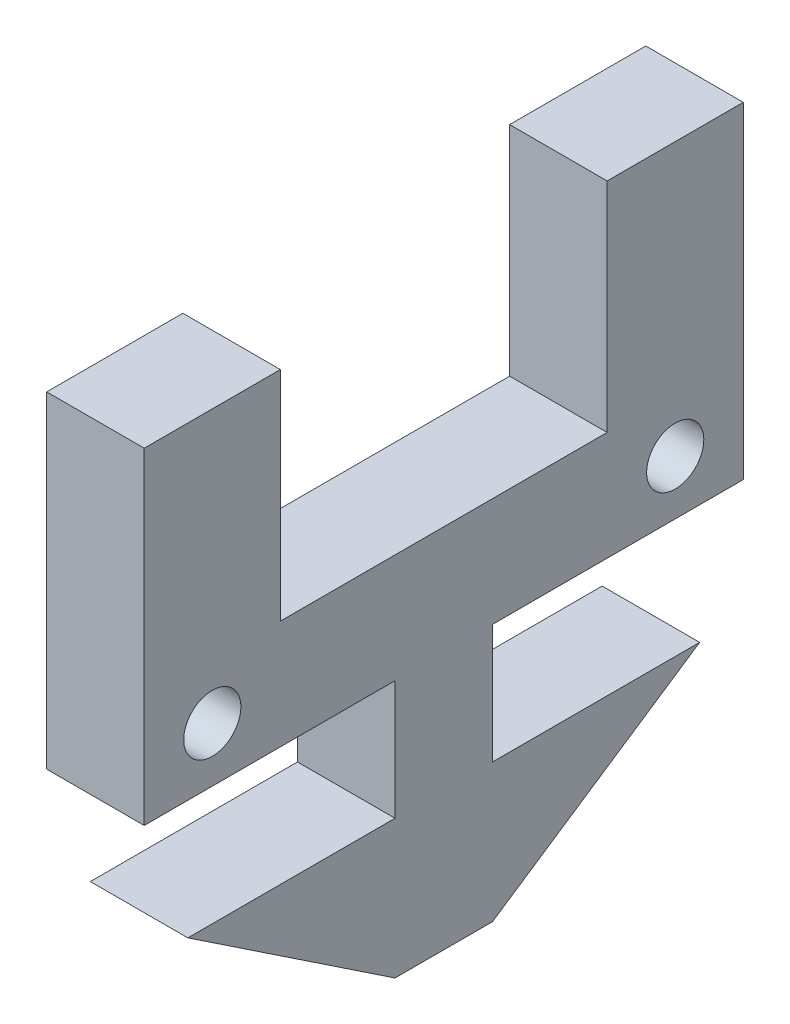
SolidWorks part; units mm, degrees
other "DetailItem2"
ref_plane "Front Plane" through (0, 0, 0) normal (0, 0, 1) x (1, 0, 0)
ref_plane "Top Plane" through (0, 0, 0) normal (0, 1, 0) x (1, 0, 0)
ref_plane "Right Plane" through (0, 0, 0) normal (1, 0, 0) x (0, 0, -1)
sketch "Sketch1" plane through (0, 0, 0) normal (1, 0, 0) x (0, 0, -1)
  line L0 (-6, 6) -> (-6, -2)
  line L1 (-11, -6) -> (11, -6)
  line L2 (-11, -6) -> (-11, 6)
  line L3 (-11, 6) -> (-6, 6)
  line L4 (11, -6) -> (11, 6)
  line L5 (-11, -6) -> (11, 6) construction
  line L6 (-11, 6) -> (11, -6) construction
  line L7 (-6, -2) -> (6, -2)
  line L8 (6, -2) -> (6, 6)
  line L9 (6, 6) -> (11, 6)
  point P0 (0, 0)
  point P8 (0, -2)
  dimension "D1" = 12
  dimension "D2" = 22
  dimension "D3" = 5
  dimension "D4" = 4
extrude "Boss-Extrude1" add sketch "Sketch1" along normal blind 3.5814
sketch "Sketch7" plane through (3.5814, 0, 0) normal (1, 0, 0) x (0, 0, -1)
  line L2 (-6, 6) -> (-11, 6) construction
  line L3 (-8.5, -4) -> (8.5, -4) construction
  circle A0 centre (-8.5, -4) radius 1.05
  circle A1 centre (8.5, -4) radius 1.05
  point P4 (0, -4)
  dimension "D1" = 2.1
  dimension "D2" = 17
  dimension "D3" = 10
extrude "Cut-Extrude5" cut sketch "Sketch7" against normal through all
sketch "Sketch8" plane through (0, 0, 0) normal (1, 0, 0) x (0, 0, -1)
  line L9 (-1.7907, -10.375) -> (-9.398, -10.375)
  line L10 (-1.7907, -6) -> (-1.7907, -10.375)
  line L11 (1.7907, -6) -> (1.7907, -10.375)
  line L12 (-9.398, -10.375) -> (-1.7907, -15.455)
  line L13 (-1.7907, -15.455) -> (1.7907, -15.455)
  line L14 (1.7907, -15.455) -> (9.398, -10.375)
  line L15 (9.398, -10.375) -> (1.7907, -10.375)
  line L16 (-11, -6) -> (11, -6) construction
  line L17 (-1.7907, -6) -> (1.7907, -6)
  point P0 (0, -8.1875)
  point P9 (0, -15.455)
  point P10 (1.7907, -8.1875)
  dimension "D1" = 3.5814
  dimension "D2" = 4.375
  dimension "D3" = 18.796
  dimension "D4" = 5.08
extrude "Boss-Extrude3" add sketch "Sketch8" along normal up to surface (3.5814 mm away) up to face at (3.5814, -4, 7.45)
